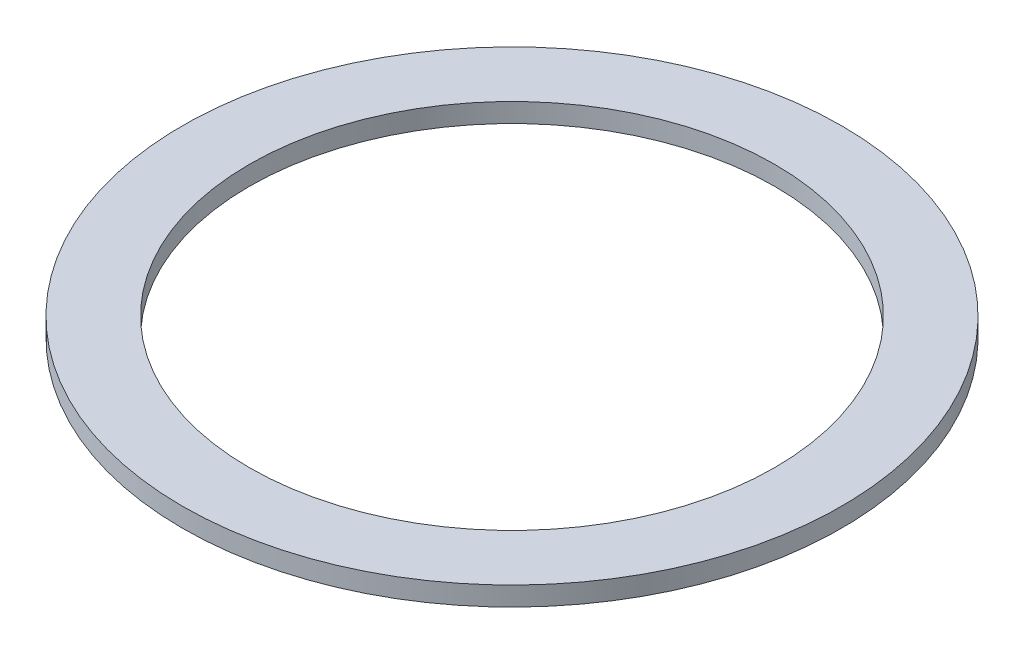
SolidWorks part; units mm, degrees
ref_plane "Front Plane" through (0, 0, 0) normal (0, 0, 1) x (1, 0, 0)
ref_plane "Top Plane" through (0, 0, 0) normal (0, 1, 0) x (1, 0, 0)
ref_plane "Right Plane" through (0, 0, 0) normal (1, 0, 0) x (0, 0, -1)
sketch "Croquis1" plane through (0, 0, 0) normal (0, 1, 0) x (1, 0, 0)
  circle A0 centre (0, 0) radius 34.5
  circle A1 centre (0, 0) radius 27.5
  dimension "D1" = 69
  dimension "D2" = 55
extrude "Saliente-Extruir1" add sketch "Croquis1" along normal blind 2
